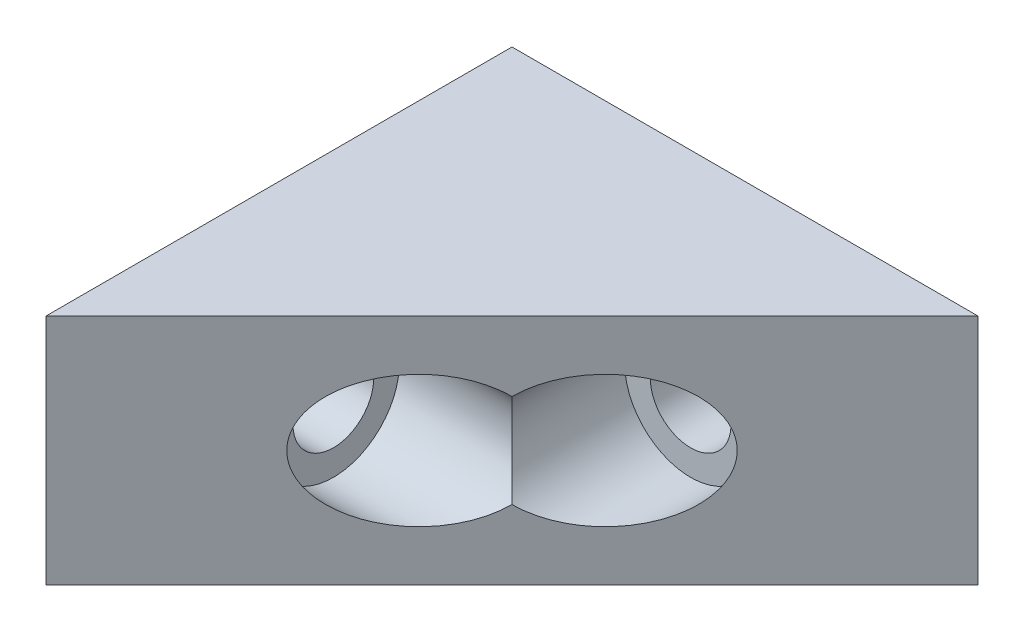
SolidWorks part; units mm, degrees
ref_plane "前视基准面" through (0, 0, 0) normal (0, 0, 1) x (1, 0, 0)
ref_plane "上视基准面" through (0, 0, 0) normal (0, 1, 0) x (1, 0, 0)
ref_plane "右视基准面" through (0, 0, 0) normal (1, 0, 0) x (0, 0, -1)
sketch "草图1" plane through (0, 0, 0) normal (0, 1, 0) x (1, 0, 0)
  line L0 (14.875, 5.775) -> (-15.125, -24.225)
  line L1 (-15.125, 5.775) -> (14.875, 5.775)
  line L2 (-15.125, 5.775) -> (-15.125, -24.225)
  dimension "D1" = 30
  dimension "D2" = 30
extrude "凸台-拉伸1" add sketch "草图1" along normal blind 15
sketch "草图2" plane through (-15.125, 0, 0) normal (-1, 0, 0) x (0, 0, 1)
  line L0 (-5.775, 15) -> (-5.775, 0) construction
  circle A0 centre (12.225, 7.5) radius 2.6
  dimension "D1" = 5.2
  dimension "D2" = 18
extrude "切除-拉伸1" cut sketch "草图2" against normal through all
sketch "草图3" plane through (0, 0, -5.775) normal (0, 0, -1) x (-1, 0, 0)
  line L0 (15.125, 15) -> (15.125, 0) construction
  circle A0 centre (-2.875, 7.5) radius 2.6
  dimension "D1" = 5.2
  dimension "D2" = 18
extrude "切除-拉伸2" cut sketch "草图3" against normal through all
ref_plane "基准面1" through (-5.125, 0, 0) normal (-1, 0, 0) x (0, 0, 1)
sketch "草图5" plane through (-5.125, 0, 0) normal (-1, 0, 0) x (0, 0, 1)
  circle A0 centre (12.225, 7.5) radius 4.25
  dimension "D1" = 8.5
extrude "切除-拉伸4" cut sketch "草图5" against normal blind 14 and the other way blind 3.5
ref_plane "基准面2" through (0, 0, 4.225) normal (0, 0, -1) x (-1, 0, 0)
sketch "草图6" plane through (0, 0, 4.225) normal (0, 0, -1) x (-1, 0, 0)
  circle A0 centre (-2.875, 7.5) radius 4.25
  dimension "D1" = 8.5
extrude "切除-拉伸5" cut sketch "草图6" against normal blind 18 and the other way blind 3.5
